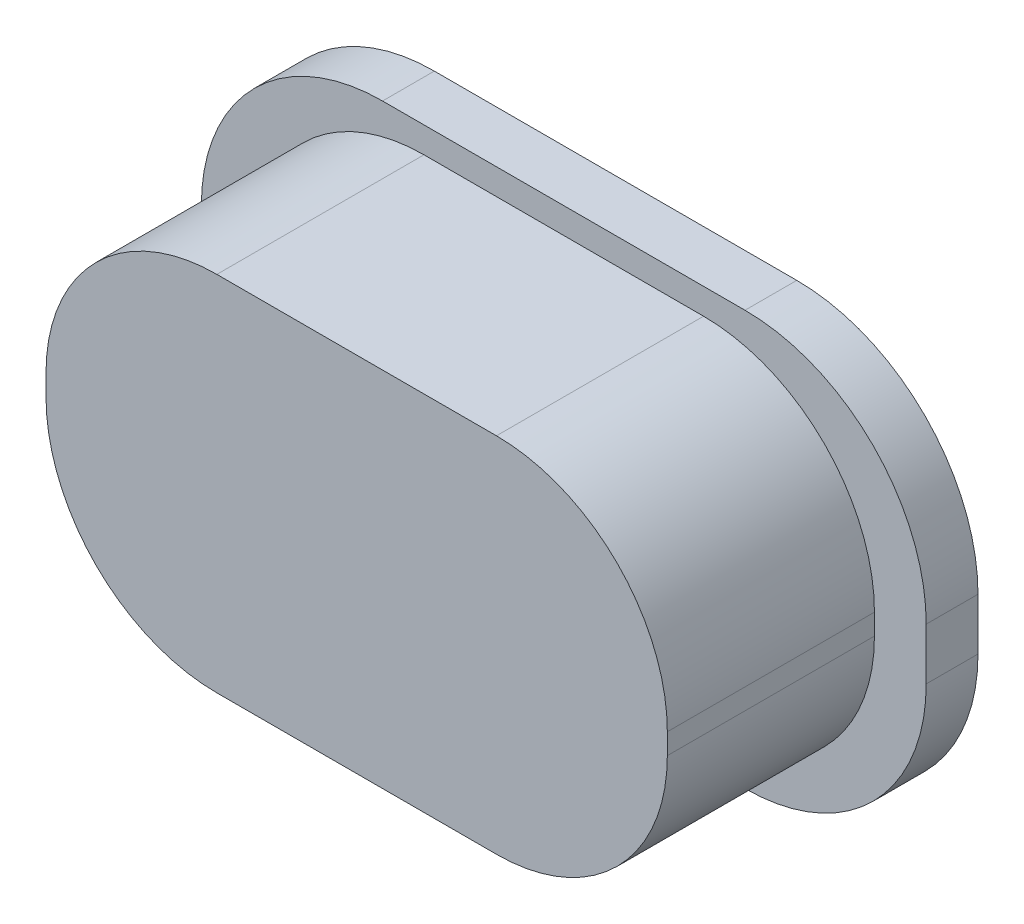
SolidWorks part; units mm, degrees
material "ABS"
ref_plane "Front Plane" through (0, 0, 0) normal (0, 0, 1) x (1, 0, 0)
ref_plane "Top Plane" through (0, 0, 0) normal (0, 1, 0) x (1, 0, 0)
ref_plane "Right Plane" through (0, 0, 0) normal (1, 0, 0) x (0, 0, -1)
sketch "Sketch1" plane through (0, 0, 0) normal (0, 0, 1) x (1, 0, 0)
  line L4 (-7, -4) -> (7, -4)
  line L5 (-7, -4) -> (-7, 4)
  line L6 (-7, 4) -> (7, 4)
  line L7 (7, -4) -> (7, 4)
  line L8 (-7, -4) -> (7, 4) construction
  line L9 (-7, 4) -> (7, -4) construction
  point P8 (0, 0)
  dimension "D2" = 8
  dimension "D1" = 14
extrude "Boss-Extrude1" add sketch "Sketch1" along normal blind 1
sketch "Sketch2" plane through (0, 0, 1) normal (0, 0, 1) x (1, 0, 0)
  line L4 (-6, -3.5) -> (6, -3.5)
  line L5 (-6, -3.5) -> (-6, 3.5)
  line L6 (-6, 3.5) -> (6, 3.5)
  line L7 (6, -3.5) -> (6, 3.5)
  line L8 (-6, -3.5) -> (6, 3.5) construction
  line L9 (-6, 3.5) -> (6, -3.5) construction
  point P8 (0, 0)
  dimension "D2" = 7
  dimension "D1" = 12
extrude "Boss-Extrude2" add sketch "Sketch2" along normal blind 4
fillet "Fillet2" radius 3.3 4 edges at (6, 3.5, 3) (-6, 3.5, 3) (6, -3.5, 3) (-6, -3.5, 3)
fillet "Fillet1" radius 3.5 4 edges at (7, -4, 0.5) (-7, -4, 0.5) (7, 4, 0.5) (-7, 4, 0.5)
